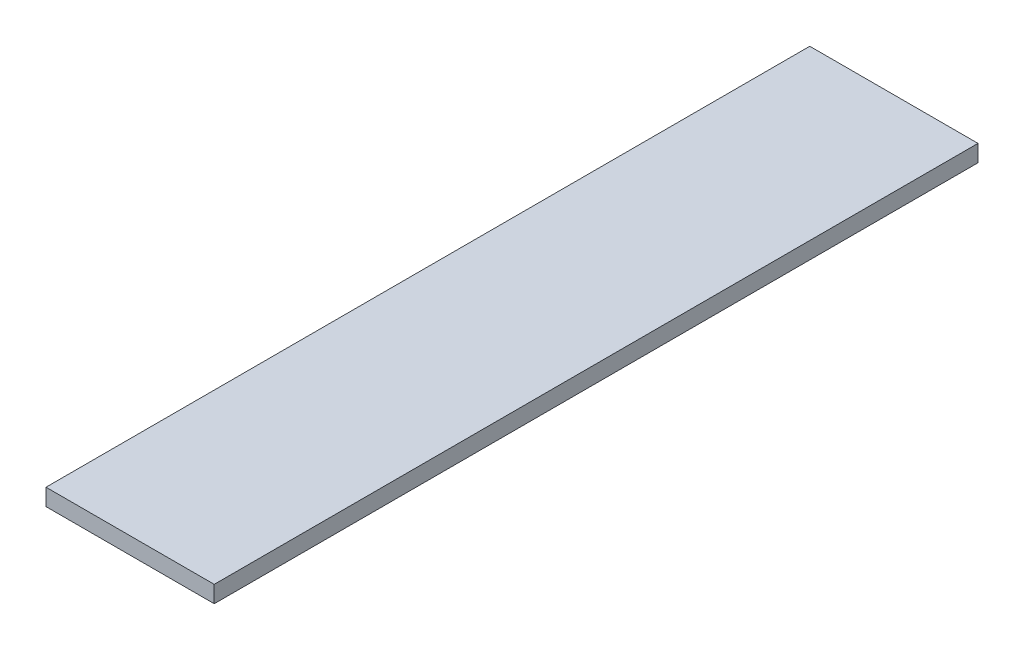
SolidWorks part; units mm, degrees
ref_plane "Front Plane" through (0, 0, 0) normal (0, 0, 1) x (1, 0, 0)
ref_plane "Top Plane" through (0, 0, 0) normal (0, 1, 0) x (1, 0, 0)
ref_plane "Right Plane" through (0, 0, 0) normal (1, 0, 0) x (0, 0, -1)
sketch "Sketch1" plane through (0, 0, 0) normal (0, 0, 1) x (1, 0, 0)
  line L1 (0, 0) -> (63.5, 0)
  line L2 (0, 0) -> (0, 6.35)
  line L3 (0, 6.35) -> (63.5, 6.35)
  line L4 (63.5, 0) -> (63.5, 6.35)
  dimension "D1" = 63.5
  dimension "D2" = 6.35
extrude "Boss-Extrude1" add sketch "Sketch1" along normal blind 288.29
